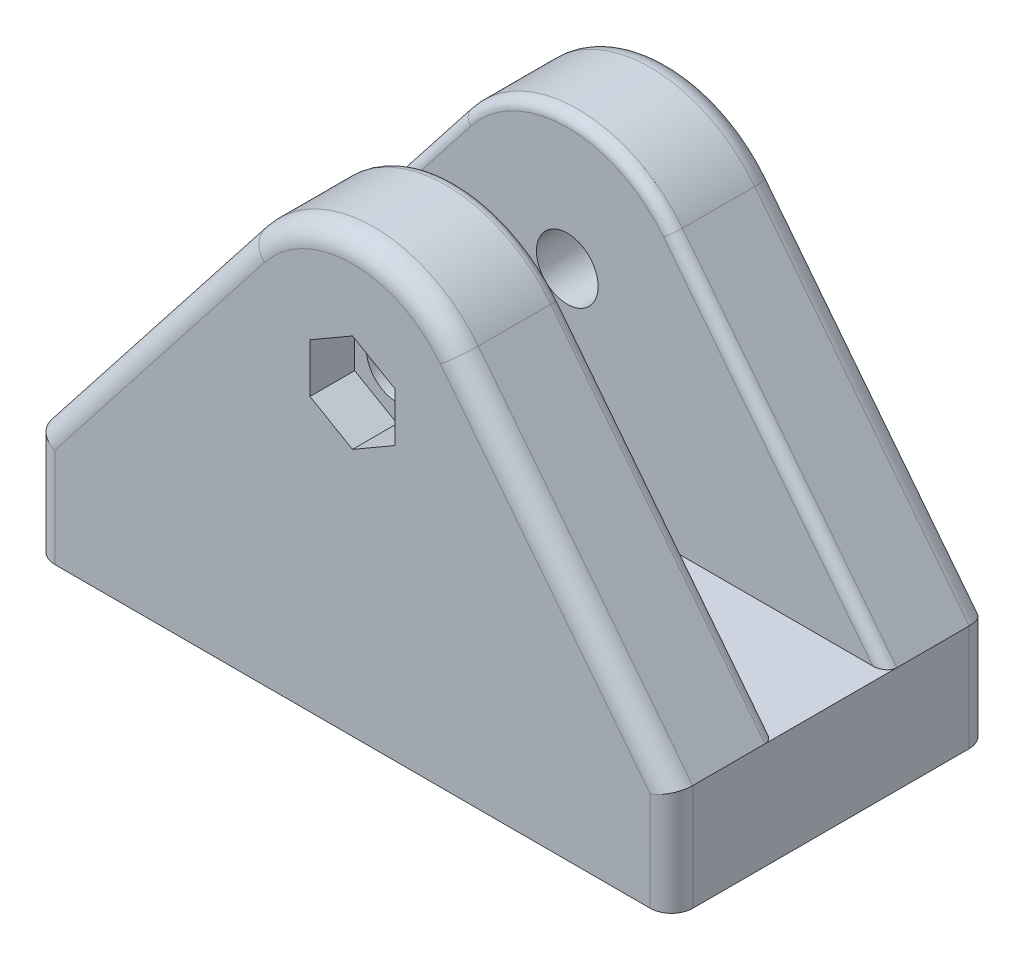
SolidWorks part; units mm, degrees
ref_plane "前基準面" through (0, 0, 0) normal (0, 0, 1) x (1, 0, 0)
ref_plane "上基準面" through (0, 0, 0) normal (0, 1, 0) x (1, 0, 0)
ref_plane "右基準面" through (0, 0, 0) normal (1, 0, 0) x (0, 0, -1)
sketch "草圖1" plane through (0, 0, 0) normal (0, 1, 0) x (1, 0, 0)
  line L1 (-30, -15) -> (30, -15)
  line L2 (-30, -15) -> (-30, 15)
  line L3 (-30, 15) -> (30, 15)
  line L4 (30, -15) -> (30, 15)
  line L5 (-30, -15) -> (30, 15) construction
  line L6 (-30, 15) -> (30, -15) construction
  point P0 (0, 0)
  dimension "D1" = 30
  dimension "D2" = 60
extrude "填料-伸長1" add sketch "草圖1" along normal blind 10
sketch "草圖2" plane through (0, 0, 15) normal (0, 0, 1) x (1, 0, 0)
  line L0 (-9.8364, 35.7134) -> (-30, 10)
  line L1 (9.8364, 35.7134) -> (30, 10)
  line L2 (-30, 10) -> (30, 10) construction
  line L3 (-30, 10) -> (30, 10)
  circle A0 centre (0, 28) radius 2.9
  arc A2 (9.8364, 35.7134) -> (-9.8364, 35.7134) centre (0, 28) ccw
  dimension "D1" = 5.8
  dimension "D3" = 25
  dimension "D2" = 28
extrude "填料-伸長2" add sketch "草圖2" against normal blind 9.8
sketch "草圖4" plane through (0, 0, -15) normal (0, 0, -1) x (-1, 0, 0)
  line L3 (30, 10) -> (9.8364, 35.7134)
  line L4 (-30, 10) -> (30, 10)
  line L5 (-9.8364, 35.7134) -> (-30, 10)
  line L6 (30, 10) -> (9.8364, 35.7134)
  line L7 (-30, 10) -> (30, 10)
  line L8 (-9.8364, 35.7134) -> (-30, 10)
  circle A1 centre (0, 28) radius 2.9
  circle A2 centre (0, 28) radius 2.9
  arc A3 (9.8364, 35.7134) -> (-9.8364, 35.7134) centre (0, 28) ccw
  arc A4 (9.8364, 35.7134) -> (-9.8364, 35.7134) centre (0, 28) ccw
  dimension "D1" = 0
  dimension "D2" = 0
extrude "填料-伸長3" add sketch "草圖4" against normal blind 9.8
sketch "草圖5" plane through (0, 0, 0) normal (0, -1, 0) x (1, 0, 0)
  line L0 (-30, 15) -> (30, 15) construction
  line L1 (20, 10) -> (-20, 10) construction
  line L2 (20, 10) -> (20, -10) construction
  line L3 (20, -10) -> (-20, -10) construction
  line L4 (-20, 10) -> (-20, -10) construction
  line L5 (20, 10) -> (-20, -10) construction
  line L6 (20, -10) -> (-20, 10) construction
  circle A0 centre (20, 10) radius 2.4
  circle A1 centre (20, -10) radius 2.4
  circle A2 centre (-20, -10) radius 2.4
  circle A3 centre (-20, 10) radius 2.4
  point P0 (0, 0)
  point P18 (0, 0)
  dimension "D4" = 4.8
  dimension "D1" = 5
  dimension "D2" = 40
  dimension "D3" = 20
extrude "除料-伸長1" cut sketch "草圖5" against normal blind 6
sketch "草圖6" plane through (0, 0, 15) normal (0, 0, 1) x (1, 0, 0)
  line L1 (0, 32.6188) -> (-4, 30.3094)
  line L2 (-4, 30.3094) -> (-4, 25.6906)
  line L3 (-4, 25.6906) -> (0, 23.3812)
  line L4 (0, 23.3812) -> (4, 25.6906)
  line L5 (4, 25.6906) -> (4, 30.3094)
  line L6 (4, 30.3094) -> (0, 32.6188)
  circle A0 centre (0, 28) radius 4 construction
  dimension "D1" = 8
extrude "除料-伸長2" cut sketch "草圖6" against normal blind 4.2
sketch "草圖7" plane through (0, 10, 0) normal (0, 1, 0) x (1, 0, 0)
  line L1 (3.1754, 0) -> (1.5877, 2.75)
  line L2 (1.5877, 2.75) -> (-1.5877, 2.75)
  line L3 (-1.5877, 2.75) -> (-3.1754, 0)
  line L4 (-3.1754, 0) -> (-1.5877, -2.75)
  line L5 (-1.5877, -2.75) -> (1.5877, -2.75)
  line L6 (1.5877, -2.75) -> (3.1754, 0)
  circle A0 centre (0, 0) radius 2.75 construction
  dimension "D1" = 5.5
extrude "除料-伸長3" cut sketch "草圖7" against normal blind 2.4
sketch "草圖8" plane through (0, 7.6, 0) normal (0, 1, 0) x (1, 0, 0)
  circle A0 centre (0, 0) radius 2.4
  dimension "D1" = 4.8
extrude "除料-伸長4" cut sketch "草圖8" against normal through all
fillet "圓角1" radius 1 6 edges at (19.9182, 22.8567, 5.2) (0, 40.5, 5.2) (19.9182, 22.8567, -5.2) (0, 40.5, -5.2) (-19.9182, 22.8567, 5.2) (-19.9182, 22.8567, -5.2)
fillet "圓角2" radius 2 10 edges at (30, 5, -15) (30, 5, 15) (-30, 5, 15) (-30, 5, -15) (-19.9182, 22.8567, -15) (0, 40.5, -15) (19.9182, 22.8567, 15) (0, 40.5, 15) (19.9182, 22.8567, -15) (-19.9182, 22.8567, 15)
chamfer "導角5" distance 1 angle 45 6 edges at (0, 10, -2.75) (-2.3816, 10, -1.375) (-2.3816, 10, 1.375) (0, 10, 2.75) (2.3816, 10, 1.375) (2.3816, 10, -1.375)
equation "\"T1\"=9.8"
equation "\"D1@填料-伸長2\"=\"T1\""
equation "\"D1@填料-伸長3\"=\"T1\""
